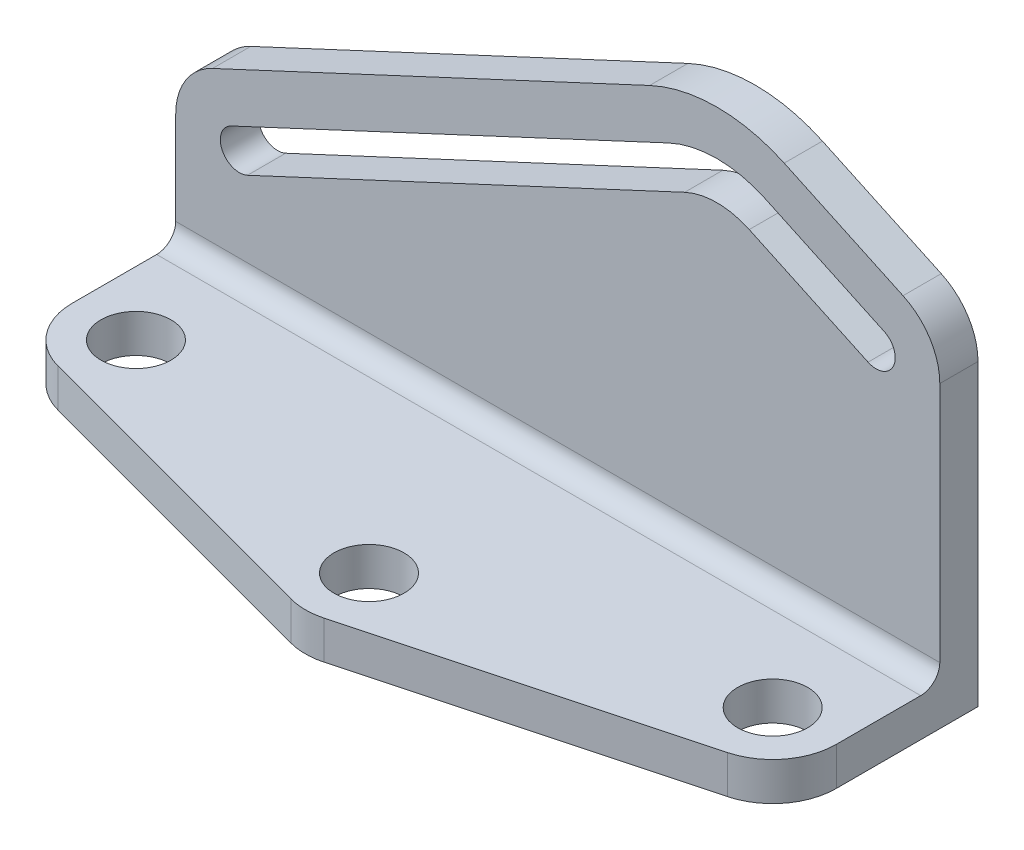
SolidWorks part; units mm, degrees
material "Промышленная бронза, UNS C22000 (90-10 Бронза)"
ref_plane "Спереди" through (0, 0, 0) normal (0, 0, 1) x (1, 0, 0)
ref_plane "Сверху" through (0, 0, 0) normal (0, 1, 0) x (1, 0, 0)
ref_plane "Справа" through (0, 0, 0) normal (1, 0, 0) x (0, 0, -1)
sketch "Эскиз1" plane through (0, 0, 0) normal (0, 0, 1) x (1, 0, 0)
  line L0 (-60, 0) -> (-60, 23.6293)
  line L1 (-54.2262, 32.6924) -> (14.4345, 64.7094)
  line L2 (35.5655, 64.7094) -> (54.2262, 56.0078)
  line L3 (60, 46.9447) -> (60, 0)
  line L4 (60, 0) -> (-60, 0)
  arc A0 (54.2262, 56.0078) -> (60, 46.9447) centre (50, 46.9447) cw
  arc A1 (14.4345, 64.7094) -> (35.5655, 64.7094) centre (25, 42.0517) cw
  arc A2 (-60, 23.6293) -> (-54.2262, 32.6924) centre (-50, 23.6293) cw
  point P10 (25, 69.6362)
  point P13 (-60, 30)
  dimension "D6" = 10
  dimension "D7" = 25
  dimension "D1" = 120
  dimension "D2" = 65
  dimension "D3" = 130
  dimension "D4" = 30
  dimension "D5" = 85
extrude "Бобышка-Вытянуть1" add sketch "Эскиз1" along normal blind 6
sketch "Эскиз2" plane through (0, 0, 0) normal (0, -1, 0) x (1, 0, 0)
  line L0 (-60, 6) -> (60, 6) construction
  line L1 (-60, 6) -> (60, 6)
  line L2 (-60, 6) -> (-60, 22.2498)
  line L3 (-52.5882, 31.909) -> (-2.5882, 45.3065)
  line L4 (2.5882, 45.3065) -> (52.5882, 31.909)
  line L5 (60, 22.2498) -> (60, 6)
  arc A0 (52.5882, 31.909) -> (60, 22.2498) centre (50, 22.2498) cw
  arc A1 (-2.5882, 45.3065) -> (2.5882, 45.3065) centre (0, 35.6472) cw
  arc A2 (-60, 22.2498) -> (-52.5882, 31.909) centre (-50, 22.2498) cw
  circle A3 centre (-50, 22.2498) radius 5.5
  circle A4 centre (0, 35.6472) radius 5.5
  circle A5 centre (50, 22.2498) radius 5.5
  point P10 (0, 46)
  dimension "D3" = 10
  dimension "D4" = 11
  dimension "D1" = 40
  dimension "D2" = 150
extrude "Бобышка-Вытянуть2" add sketch "Эскиз2" against normal blind 6
fillet "Скругление1" radius 3 1 edges at (0, 6, 6)
sketch "Эскиз3" plane through (0, 0, 6) normal (0, 0, 1) x (1, 0, 0)
  line L2 (51.2679, 49.6636) -> (32.6071, 58.3652)
  line L3 (17.3929, 58.3652) -> (-51.2679, 26.3482)
  line L4 (18.6607, 55.6463) -> (-50, 23.6293)
  line L5 (50, 46.9447) -> (31.3393, 55.6463)
  line L6 (18.6607, 55.6463) -> (-50, 23.6293) construction
  line L7 (50, 46.9447) -> (31.3393, 55.6463) construction
  line L8 (48.7321, 44.2258) -> (30.0714, 52.9274)
  line L9 (19.9286, 52.9274) -> (-48.7321, 20.9104)
  arc A1 (32.6071, 58.3652) -> (17.3929, 58.3652) centre (25, 42.0517) ccw
  arc A2 (31.3393, 55.6463) -> (18.6607, 55.6463) centre (25, 42.0517) ccw
  arc A3 (31.3393, 55.6463) -> (18.6607, 55.6463) centre (25, 42.0517) ccw construction
  arc A4 (30.0714, 52.9274) -> (19.9286, 52.9274) centre (25, 42.0517) ccw
  arc A5 (51.2679, 49.6636) -> (48.7321, 44.2258) centre (50, 46.9447) cw
  arc A6 (-51.2679, 26.3482) -> (-48.7321, 20.9104) centre (-50, 23.6293) ccw
  dimension "D1" = 10
  dimension "D2" = 3
  dimension "D3" = 3
extrude "Вырез-Вытянуть1" cut sketch "Эскиз3" against normal through all
